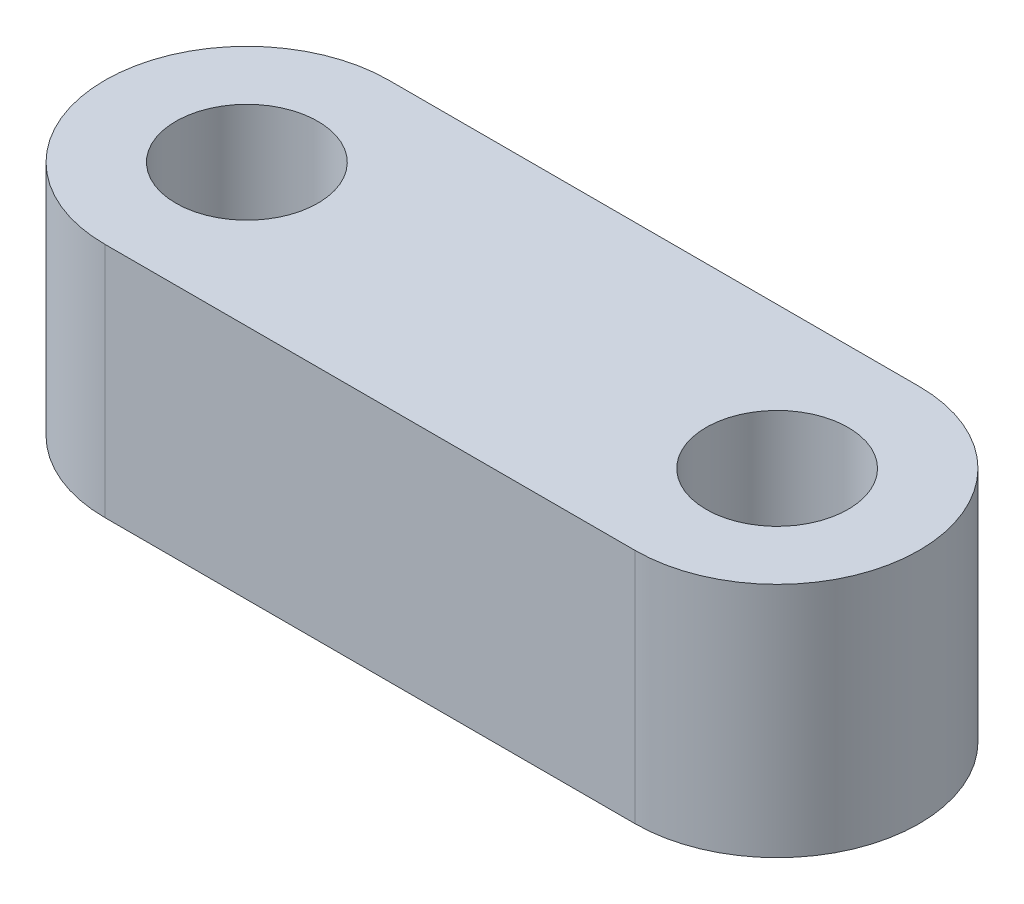
SolidWorks part; units mm, degrees
ref_plane "Front" through (0, 0, 0) normal (0, 0, 1) x (1, 0, 0)
ref_plane "Top" through (0, 0, 0) normal (0, 1, 0) x (1, 0, 0)
ref_plane "Right" through (0, 0, 0) normal (1, 0, 0) x (0, 0, -1)
sketch "Sketch1" plane through (0, 0, 0) normal (0, 1, 0) x (1, 0, 0)
  line L0 (0, 60) -> (224, 60)
  line L1 (0, -60) -> (224, -60)
  arc A0 (0, 60) -> (0, -60) centre (0, 0) ccw
  arc A1 (224, -60) -> (224, 60) centre (224, 0) ccw
  circle A2 centre (0, 0) radius 30
  circle A3 centre (224, 0) radius 30
  dimension "D1" = 224
  dimension "D2" = 120
  dimension "D3" = 120
extrude "Boss-Extrude1" add sketch "Sketch1" along normal blind 100
